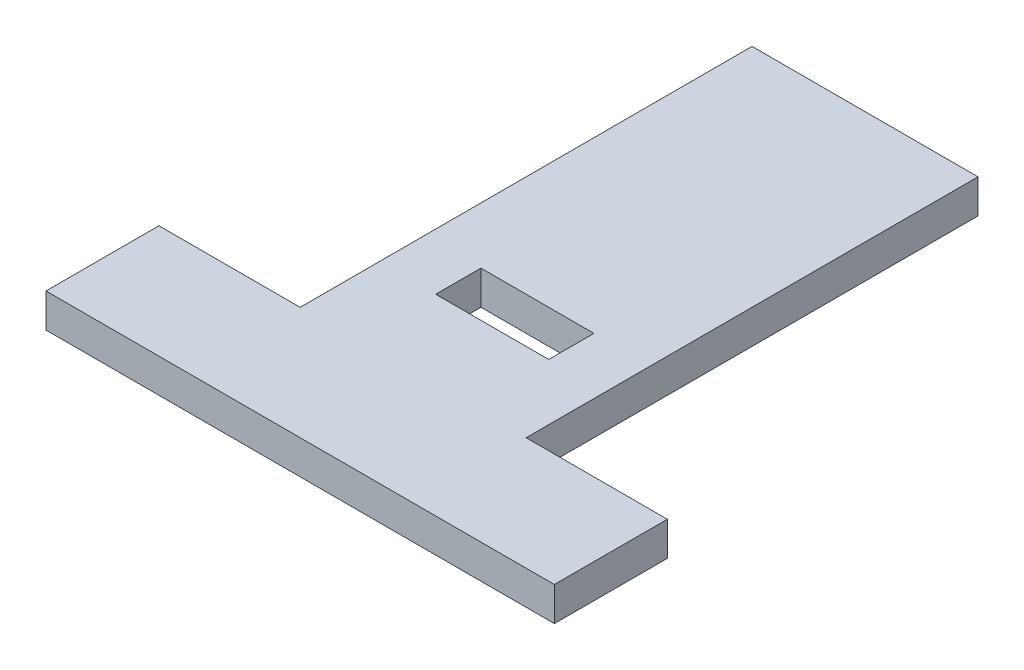
SolidWorks part; units mm, degrees
ref_plane "Front Plane" through (0, 0, 0) normal (0, 0, 1) x (1, 0, 0)
ref_plane "Top Plane" through (0, 0, 0) normal (0, 1, 0) x (1, 0, 0)
ref_plane "Right Plane" through (0, 0, 0) normal (1, 0, 0) x (0, 0, -1)
sketch "Sketch1" plane through (0, 0, 0) normal (0, 1, 0) x (1, 0, 0)
  line L1 (-22.5, 25) -> (22.5, 25)
  line L2 (-22.5, 25) -> (-22.5, -25)
  line L3 (-22.5, -25) -> (22.5, -25)
  line L4 (22.5, 25) -> (22.5, -25)
  line L5 (-22.5, 25) -> (22.5, -25) construction
  line L6 (-22.5, -25) -> (22.5, 25) construction
  point P0 (0, 0)
  dimension "D1" = 45
  dimension "D2" = 50
extrude "Boss-Extrude1" add sketch "Sketch1" along normal blind 3
sketch "Sketch4" plane through (0, 3, 0) normal (0, 1, 0) x (1, 0, 0)
  line L0 (-22.5, -25) -> (22.5, -25) construction
  line L1 (-22.5, 25) -> (-10, 25)
  line L2 (-22.5, 25) -> (-22.5, -15.0037)
  line L3 (-22.5, -15.0037) -> (-10, -15.0037)
  line L4 (-10, 25) -> (-10, -15.0037)
  line L5 (22.5, 25) -> (10, 25)
  line L6 (22.5, 25) -> (22.5, -15)
  line L7 (22.5, -15) -> (10, -15)
  line L8 (10, 25) -> (10, -15)
  line L10 (-5, -4) -> (5, -4)
  line L11 (-5, -4) -> (-5, -8)
  line L12 (-5, -8) -> (5, -8)
  line L13 (5, -4) -> (5, -8)
  point P16 (-5, -6)
  dimension "D1" = 20
  dimension "D2" = 9.9963
  dimension "D3" = 10
  dimension "D4" = 12.5
  dimension "D5" = 4
  dimension "D6" = 10
  dimension "D7" = 17
  dimension "D8" = 5
extrude "Cut-Extrude1" cut sketch "Sketch4" against normal blind 3
